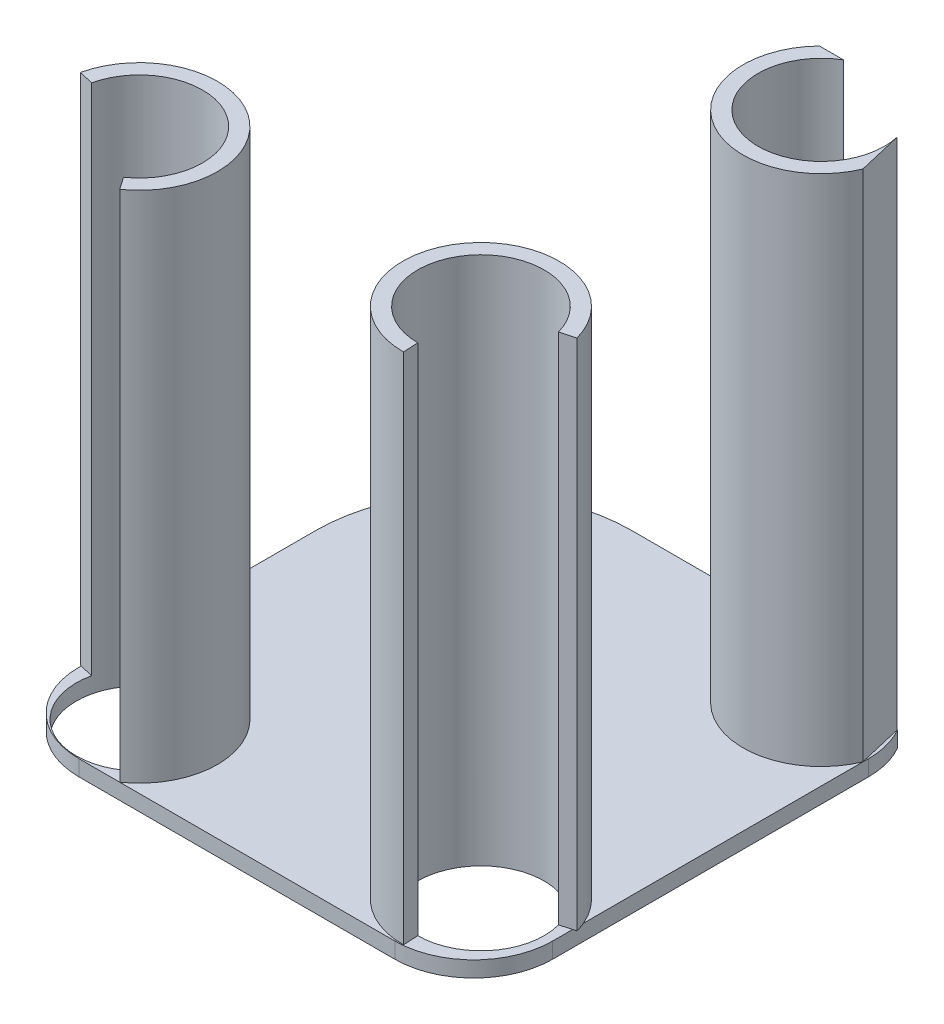
SolidWorks part; units mm, degrees
ref_plane "Front Plane" through (0, 0, 0) normal (0, 0, 1) x (1, 0, 0)
ref_plane "Top Plane" through (0, 0, 0) normal (0, 1, 0) x (1, 0, 0)
ref_plane "Right Plane" through (0, 0, 0) normal (1, 0, 0) x (0, 0, -1)
sketch "Sketch2" plane through (0, 0, 0) normal (0, 1, 0) x (1, 0, 0)
  line L1 (-10, 30) -> (20, 30)
  line L2 (-30, 10) -> (-30, -20)
  line L3 (-20, -30) -> (20, -30)
  line L4 (30, 20) -> (30, -20)
  line L5 (-30, 30) -> (30, -30) construction
  line L6 (-30, -30) -> (30, 30) construction
  arc A0 (-10, 30) -> (-30, 10) centre (-10, 10) ccw
  arc A1 (-30, -20) -> (-20, -30) centre (-20, -20) ccw
  arc A2 (20, -30) -> (30, -20) centre (20, -20) ccw
  arc A3 (20, 30) -> (30, 20) centre (20, 20) cw
  point P0 (0, 0)
  dimension "D3" = 20
  dimension "D4" = 10
  dimension "D1" = 60
  dimension "D2" = 60
extrude "Boss-Extrude1" add sketch "Sketch2" along normal blind 2
sketch "Sketch4" plane through (0, 2, 0) normal (0, 1, 0) x (1, 0, 0)
  circle A0 centre (-22.4496, -20.0472) radius 11
  circle A1 centre (20.5475, -19.2406) radius 11
  circle A2 centre (19.8692, 19.7716) radius 11
  dimension "D1" = 22
extrude "Boss-Extrude8" [suppressed] add sketch "Sketch4" along normal blind 65
sketch "Sketch3" plane through (0, 2, 0) normal (0, 1, 0) x (1, 0, 0)
  circle A0 centre (-22.4496, -20.0472) radius 7.5566
  circle A2 centre (20.5475, -19.2406) radius 7.5566
  circle A4 centre (19.8692, 19.7716) radius 7.5566
extrude "Cut-Extrude2" [suppressed] cut sketch "Sketch3" against normal through all and the other way through all
sketch "Sketch5" plane through (0, 2, 0) normal (0, 1, 0) x (1, 0, 0)
  line L0 (-30.1164, -19.6808) -> (-28.2634, -20.1009)
  line L1 (-14.8127, -30) -> (-15.8968, -28.4396)
  line L2 (-20, -30) -> (20, -30) construction
  line L3 (20.9771, -29.8639) -> (20.8756, -27.9644)
  line L4 (28.5957, -17.8666) -> (30.4292, -17.3683)
  line L5 (13.7644, 30) -> (16.8063, 30)
  line L7 (20, 30) -> (-10, 30) construction
  line L8 (28.6649, 24.9363) -> (29.9945, 19.2581)
  arc A0 (-15.8968, -28.4396) -> (-28.2634, -20.1009) centre (-20.4614, -21.8697) ccw
  arc A1 (28.5957, -17.8666) -> (20.8756, -27.9644) centre (20.8756, -19.9644) ccw
  arc A2 (16.8063, 30) -> (28.6649, 24.9363) centre (20.8756, 23.1123) ccw
  arc A3 (13.7644, 30) -> (29.9945, 19.2581) centre (20.8756, 23.1123) ccw
  arc A4 (30.4292, -17.3683) -> (20.9771, -29.8639) centre (20.8756, -19.9644) ccw
  arc A5 (-14.8127, -30) -> (-30.1164, -19.6808) centre (-20.4614, -21.8697) ccw
  dimension "D1" = 16
  dimension "D2" = 1.9
extrude "Boss-Extrude9" add sketch "Sketch5" along normal blind 65
sketch "Sketch6" plane through (0, 2, 0) normal (0, 1, 0) x (1, 0, 0)
  circle A0 centre (20.8756, 23.1123) radius 8
  circle A1 centre (-20.4614, -21.8697) radius 8
  circle A2 centre (20.8756, -19.9644) radius 8
  circle A3 centre (-20.4614, -21.8697) radius 8 construction
extrude "Cut-Extrude3" cut sketch "Sketch6" against normal through all
sketch "Sketch7" plane through (0, 0, 0) normal (0, -1, 0) x (1, 0, 0)
  circle A0 centre (6.6002, -6.0679) radius 2
  dimension "D1" = 4
extrude "Boss-Extrude10" add sketch "Sketch7" along normal blind 10
sketch "Sketch8" plane through (0, 0, 0) normal (0, -1, 0) x (1, 0, 0)
  circle A0 centre (-5.4015, 9.1209) radius 2
  dimension "D1" = 4
extrude "Boss-Extrude11" add sketch "Sketch8" along normal blind 10
